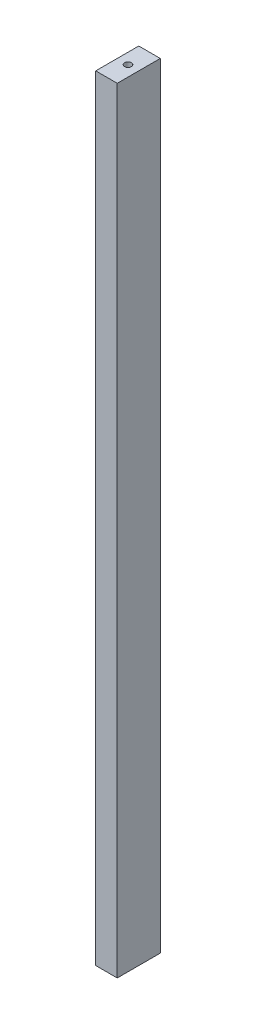
SolidWorks part; units mm, degrees
ref_plane "Спереди" through (0, 0, 0) normal (0, 0, 1) x (1, 0, 0)
ref_plane "Сверху" through (0, 0, 0) normal (0, 1, 0) x (1, 0, 0)
ref_plane "Справа" through (0, 0, 0) normal (1, 0, 0) x (0, 0, -1)
other "Configuration Table"
sketch "Эскиз1" plane through (0, 0, 0) normal (0, 1, 0) x (1, 0, 0)
  line L1 (12.5, 25) -> (-12.5, 25)
  line L2 (12.5, 25) -> (12.5, -25)
  line L3 (12.5, -25) -> (-12.5, -25)
  line L4 (-12.5, 25) -> (-12.5, -25)
  line L5 (12.5, 25) -> (-12.5, -25) construction
  line L6 (12.5, -25) -> (-12.5, 25) construction
  point P0 (0, 0)
extrude "Бобышка-Вытянуть1" add sketch "Эскиз1" along normal blind 900
sketch "Эскиз2" plane through (0, 0, 0) normal (0, -1, 0) x (1, 0, 0)
  circle A0 centre (0, 0) radius 4
extrude "Вырез-Вытянуть1" cut sketch "Эскиз2" against normal blind 10
sketch "Эскиз3" plane through (0, 900, 0) normal (0, 1, 0) x (1, 0, 0)
  circle A0 centre (0, 0) radius 4
extrude "Вырез-Вытянуть2" cut sketch "Эскиз3" against normal blind 10
